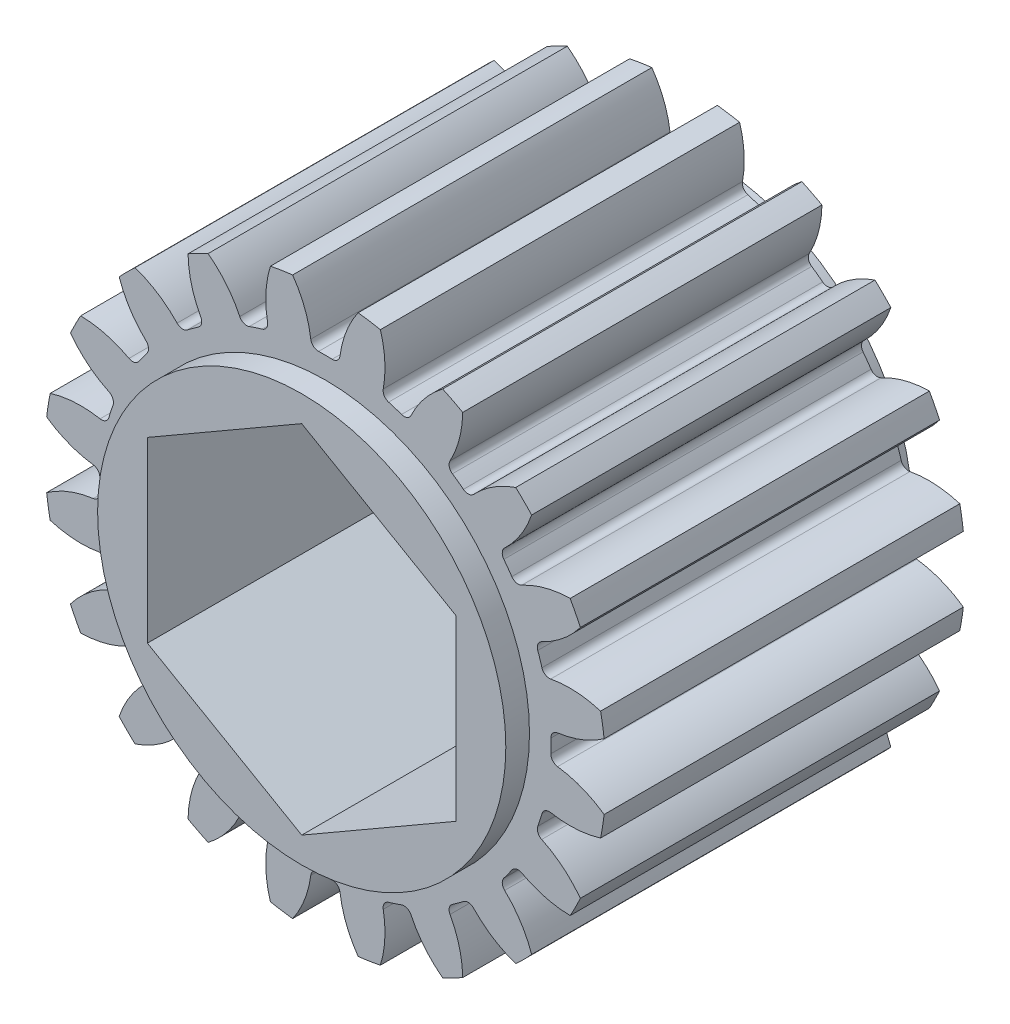
SolidWorks part; units mm, degrees
material "AISI 4130 Acero normalizado a 870C"
ref_plane "Alzado" through (0, 0, 0) normal (0, 0, 1) x (1, 0, 0)
ref_plane "Planta" through (0, 0, 0) normal (0, 1, 0) x (1, 0, 0)
ref_plane "Vista lateral" through (0, 0, 0) normal (1, 0, 0) x (0, 0, -1)
sketch "Croquis1" plane through (0, 0, 0) normal (0, 0, 1) x (1, 0, 0)
  circle A0 centre (0, 0) radius 7.9375 construction
  circle A1 centre (0, 0) radius 8.7312
  dimension "D" = 15.875
  dimension "OD" = 17.4625
extrude "Saliente-Extruir1" add sketch "Croquis1" along normal mid plane 11.176
sketch "Croquis2" plane through (0, 0, 0) normal (0, 0, 1) x (1, 0, 0)
  line L0 (0, 0) -> (0, 8.7312) construction
  line L1 (0, 0) -> (2.6981, 8.3039) construction
  line L2 (0, 0) -> (1.3659, 8.6238) construction
  line L3 (-0.4337, 7.0057) -> (0, 0) construction
  line L4 (-0.6228, 7.913) -> (0.6228, 7.913) construction
  line L5 (0.6228, 7.913) -> (1.853, 7.7182) construction
  line L6 (-0.9035, 8.6844) -> (0, 6.202) construction
  circle A0 centre (0, 0) radius 8.7312 construction
  arc A2 (0.4337, 7.0057) -> (-0.4337, 7.0057) centre (0, 0) ccw
  circle A5 centre (0, 0) radius 7.9375 construction
  arc A6 (-1.0192, 8.6716) -> (-0.4337, 7.0057) centre (-3.6652, 6.8057) cw
  arc A7 (1.0192, 8.6716) -> (0.4337, 7.0057) centre (3.6652, 6.8057) ccw
  arc A8 (1.0192, 8.6716) -> (-1.0192, 8.6716) centre (0, 0) ccw
  dimension "D1" = 18
  dimension "D2" = 9
  dimension "B" = 0.9184
  dimension "Pressure Angle" = 20
extrude "Cortar-Extruir1" cut sketch "Croquis2" against normal through all both and the other way through all
fillet "Redondeo1" radius 0.2381 2 edges at (0.4337, 7.0057, 0) (-0.4337, 7.0057, 0)
pattern_circular "MatrizC1" count 20 over 360 about axis through (0, 0, 0) along (0, 0, 1) of "Cortar-Extruir1", "Redondeo1"
sketch "Croquis3" plane through (0, 0, 0) normal (0, 0, 1) x (1, 0, 0)
  circle A0 centre (0, 0) radius 6.35
  dimension "sp" = 12.7
extrude "Saliente-Extruir2" add sketch "Croquis3" along normal mid plane 12.6492
sketch "Croquis4" plane through (0, 0, 0) normal (0, 0, 1) x (1, 0, 0)
  line L1 (0, 5.5433) -> (-4.8006, 2.7716)
  line L2 (-4.8006, 2.7716) -> (-4.8006, -2.7716)
  line L3 (-4.8006, -2.7716) -> (0, -5.5433)
  line L4 (0, -5.5433) -> (4.8006, -2.7716)
  line L5 (4.8006, -2.7716) -> (4.8006, 2.7716)
  line L6 (4.8006, 2.7716) -> (0, 5.5433)
  circle A0 centre (0, 0) radius 4.8006 construction
  dimension "D1" = 9.6012
extrude "Cortar-Extruir2" cut sketch "Croquis4" against normal through all both and the other way through all
sketch "Croquis5" [suppressed] plane through (0, 0, 5.588) normal (0, 0, 1) x (1, 0, 0)
  circle A0 centre (0, 0) radius 7.9375
  circle A1 centre (0, 0) radius 36.2931
  circle A2 centre (0, 0) radius 40.4813 construction
  dimension "D1" = 15.875
  dimension "D2" = 4.1881
extrude "Cortar-Extruir3" [suppressed] cut sketch "Croquis5" against normal blind 4.3
fillet "Redondeo2" [suppressed] radius 3
mirror "Simetría1" [suppressed] about plane through (0, 0, 0) normal (0, 0, 1)
equation "\"Number of teeth\" = 20"
equation "\"Diametral Pitch\"= 32"
equation "\"Pressure Angle\"= 20"
equation "\"D@Croquis1\"=\"Number of teeth\"/\"Diametral Pitch\""
equation "\"OD@Croquis1\"=(\"Number of teeth\"+2) /\"Diametral Pitch\""
equation "\"D2@Croquis2\"=(360 / \"Number of teeth\")/ 2."
equation "\"D1@Croquis2\"=360 / \"Number of teeth\""
equation "\"B@Croquis2\"=1.157 / \"Diametral Pitch\""
equation "\"Pressure Angle@Croquis2\" = \"Pressure Angle\""
equation "\"D1@Redondeo1\"=(pi / \"Diametral Pitch\") * .0955"
equation "\"D1@MatrizC1\"=\"Number of teeth\""
